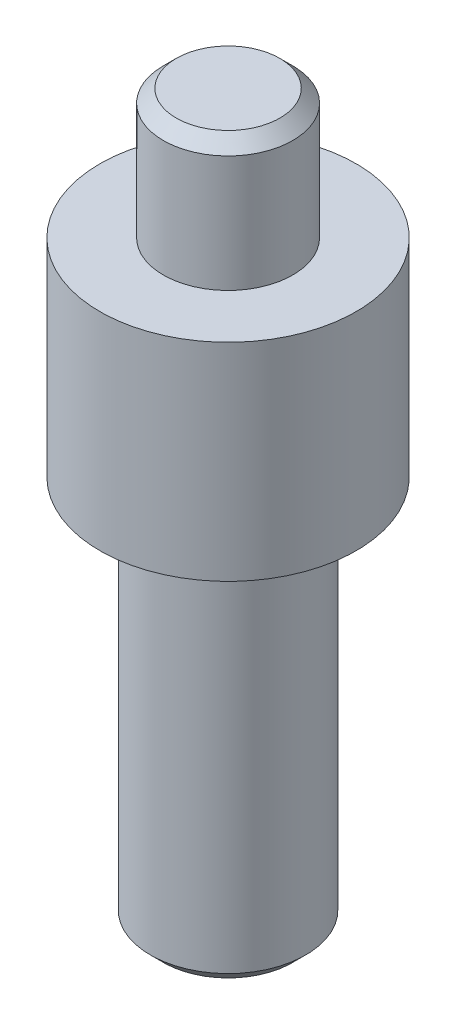
SolidWorks part; units mm, degrees
material "Lega 1060"
ref_plane "Piano frontale" through (0, 0, 0) normal (0, 0, 1) x (1, 0, 0)
ref_plane "Piano superiore" through (0, 0, 0) normal (0, 1, 0) x (1, 0, 0)
ref_plane "Piano destro" through (0, 0, 0) normal (1, 0, 0) x (0, 0, -1)
sketch "Schizzo1" plane through (0, 0, 0) normal (0, 1, 0) x (1, 0, 0)
  circle A0 centre (0, 0) radius 3
extrude "Estrusione-Estrusione1" add sketch "Schizzo1" against normal blind 15
cosmetic thread "Filettatura cosmetica1" parameters "D1"=15, "D2"=4.891
sketch "Schizzo2" plane through (0, 0, 0) normal (0, 1, 0) x (1, 0, 0)
  circle A1 centre (0, 0) radius 4.95
extrude "Estrusione-Estrusione2" add sketch "Schizzo2" along normal blind 8
chamfer "Smusso1" distance 0.5 angle 45 1 edges at (-3, -15, 0)
sketch "Schizzo4" plane through (0, 8, 0) normal (0, 1, 0) x (1, 0, 0)
  circle A0 centre (0, 0) radius 2.5
  dimension "D1" = 5
extrude "Estrusione-Estrusione5" add sketch "Schizzo4" along normal blind 5
chamfer "Smusso2" distance 0.5 angle 45 1 edges at (-2.5, 13, 0)
